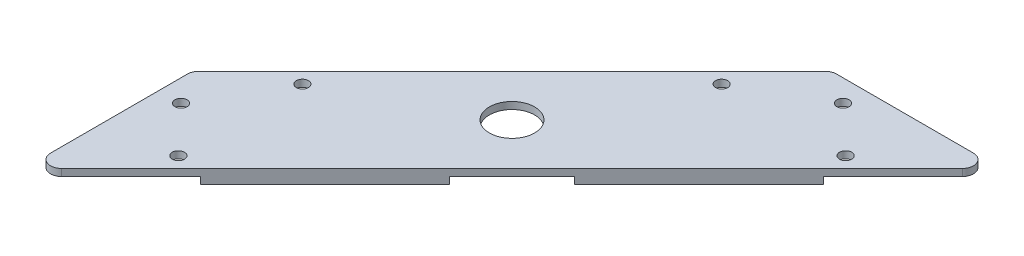
SolidWorks part; units mm, degrees
ref_plane "Front" through (0, 0, 0) normal (0, 0, 1) x (1, 0, 0)
ref_plane "Top" through (0, 0, 0) normal (0, 1, 0) x (1, 0, 0)
ref_plane "Right" through (0, 0, 0) normal (1, 0, 0) x (0, 0, -1)
sketch "Sketch1" plane through (0, 0, 0) normal (0, 1, 0) x (1, 0, 0)
  line L0 (0, 0) -> (76.2, 0)
  line L1 (76.2, 0) -> (-145, -221.2)
  line L2 (-145, -221.2) -> (-145, -145)
  line L3 (-145, -145) -> (0, 0)
  line L4 (0, 0) -> (-145, 0) construction
  line L5 (-145, 0) -> (-145, -145) construction
  line L6 (-72.5, -72.5) -> (-34.4, -110.6) construction
  circle A0 centre (-53.45, -91.55) radius 10.25
  dimension "D3" = 20.5
  dimension "D1" = 145
  dimension "D2" = 76.2
extrude "Boss-Extrude1" add sketch "Sketch1" along normal blind 3.175
sketch "Sketch2" plane through (0, 0, 0) normal (0, -1, 0) x (1, 0, 0)
  line L0 (-58.3579, 58.3579) -> (-20.2579, 96.4579)
  line L1 (-86.6421, 86.6421) -> (-48.5421, 124.7421)
  line L2 (-48.5421, 124.7421) -> (-145, 221.2)
  line L3 (-58.3579, 58.3579) -> (0, 0)
  line L4 (-145, 145) -> (0, 0)
  line L5 (0, 0) -> (76.2, 0)
  line L6 (76.2, 0) -> (-145, 221.2)
  line L7 (-145, 221.2) -> (-145, 145)
  line L8 (-145, 145) -> (-86.6421, 86.6421)
  line L9 (0, 0) -> (76.2, 0)
  line L10 (76.2, 0) -> (-20.2579, 96.4579)
  line L11 (-145, 221.2) -> (-145, 145)
  line L12 (-40, 40) -> (36.2, 40)
  line L13 (-105, 105) -> (-105, 181.2)
  circle A0 centre (-53.45, 91.55) radius 10.25 construction
  point P14 (0, 0)
  point P15 (0, 0)
  line M9 (-145, 145) -> (0, 0)
  line M11 (76.2, 0) -> (-145, 221.2)
  dimension "D2" = 20
  dimension "D3" = 20
  dimension "D4" = 40
  dimension "D5" = 40
  dimension "D1" = 0
extrude "Boss-Extrude2" add sketch "Sketch2" along normal blind 3.175 contours L12 L10 L0 M9 | L13 L8 L1 M11
fillet "Fillet1" radius 5 4 edges at (-145, 1.5875, 145) (-145, 1.5875, 221.2) (76.2, 1.5875, 0) (0, 1.5875, 0)
sketch "Sketch3" plane through (0, 0, 0) normal (0, -1, 0) x (-1, 0, 0)
  line L0 (135, -135) -> (135, -211.2) construction
  line L1 (105, -105) -> (143.5355, -143.5355) construction
  line L2 (136.4645, -212.6645) -> (105, -181.2) construction
  line L3 (115, -115) -> (115, -191.2) construction
  line L4 (72.5, -72.5) -> (34.4, -110.6) construction
  line L5 (58.3579, -58.3579) -> (86.6421, -86.6421) construction
  line L6 (48.5421, -124.7421) -> (20.2579, -96.4579) construction
  line L7 (145, -147.0711) -> (145, -209.1289) construction
  line L8 (30, -30) -> (-46.2, -30) construction
  line L9 (10, -10) -> (-66.2, -10) construction
  circle A0 centre (115, -125) radius 2.75
  circle A1 centre (115, -181.2) radius 2.75
  circle A2 centre (135, -160) radius 2.75
  circle A3 centre (-15, -10) radius 2.75
  circle A4 centre (-36.2, -30) radius 2.75
  circle A5 centre (20, -30) radius 2.75
  dimension "D3" = 5.5
  dimension "D4" = 10
  dimension "D5" = 10
  dimension "D6" = 25
  dimension "D1" = 20
  dimension "D2" = 10
extrude "Cut-Extrude1" cut sketch "Sketch3" against normal up to next
